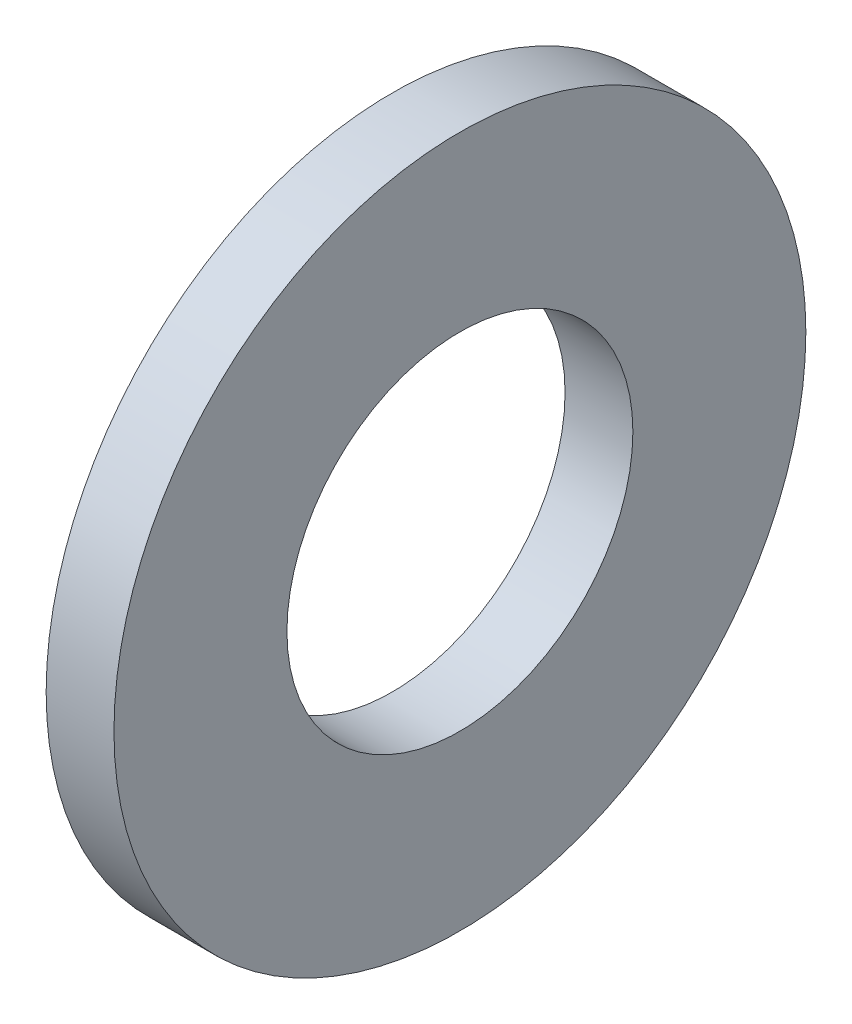
SolidWorks part; units mm, degrees
ref_plane "Plane1" through (0, 0, 0) normal (0, 0, 1) x (1, 0, 0)
ref_plane "Plane2" through (0, 0, 0) normal (0, 1, 0) x (1, 0, 0)
ref_plane "Plane3" through (0, 0, 0) normal (1, 0, 0) x (0, 0, -1)
sketch "Sketch1" plane through (0, 0, 0) normal (0, 0, 1) x (1, 0, 0)
  line L0 (-34.925, 0) -> (9.525, 0) construction
  line L1 (0, 3.175) -> (0, 6.35)
  line L2 (0, 6.35) -> (-1.2446, 6.35)
  line L3 (-1.2446, 6.35) -> (-1.2446, 3.175)
  line L4 (-1.2446, 3.175) -> (0, 3.175)
  dimension "Thickness" = 1.2446
  dimension "Inside_dia" = 6.35
  dimension "Outside_dia" = 12.7
revolve "Base-Revolve" add sketch "Sketch1" angle 360 about L0
